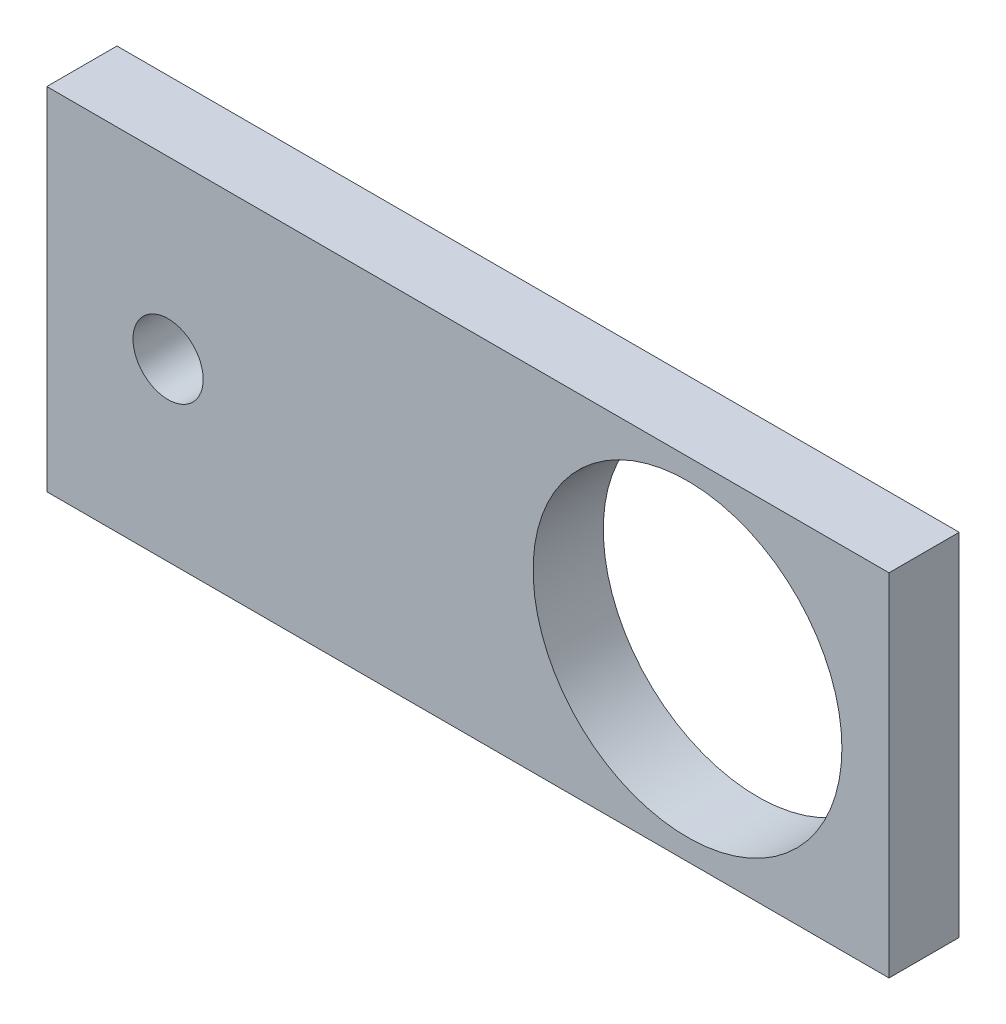
SolidWorks part; units mm, degrees
ref_plane "Front Plane" through (0, 0, 0) normal (0, 0, 1) x (1, 0, 0)
ref_plane "Top Plane" through (0, 0, 0) normal (0, 1, 0) x (1, 0, 0)
ref_plane "Right Plane" through (0, 0, 0) normal (1, 0, 0) x (0, 0, -1)
sketch "Sketch1" plane through (0, 0, 0) normal (0, 0, 1) x (1, 0, 0)
  line L1 (30, 12.5) -> (-30, 12.5)
  line L2 (30, 12.5) -> (30, -12.5)
  line L3 (30, -12.5) -> (-30, -12.5)
  line L4 (-30, 12.5) -> (-30, -12.5)
  line L5 (30, 12.5) -> (-30, -12.5) construction
  line L6 (30, -12.5) -> (-30, 12.5) construction
  circle A0 centre (-21.3599, 0) radius 2.5
  circle A1 centre (15.6442, 0) radius 11
  point P0 (0, 0)
  dimension "D3" = 5
  dimension "D4" = 22
  dimension "D1" = 60
  dimension "D2" = 25
extrude "Boss-Extrude2" add sketch "Sketch1" along normal blind 5
